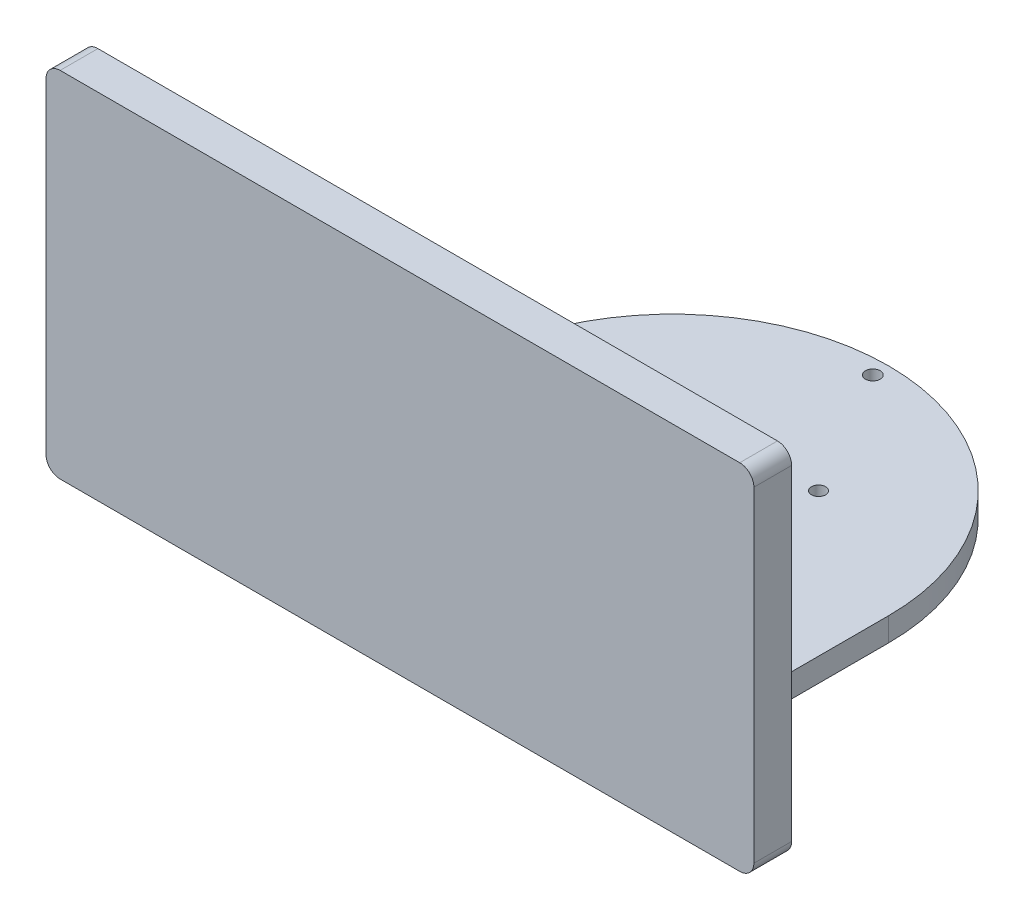
SolidWorks part; units mm, degrees
ref_plane "Front Plane" through (0, 0, 0) normal (0, 0, 1) x (1, 0, 0)
ref_plane "Top Plane" through (0, 0, 0) normal (0, 1, 0) x (1, 0, 0)
ref_plane "Right Plane" through (0, 0, 0) normal (1, 0, 0) x (0, 0, -1)
sketch "Sketch1" plane through (0, 0, 0) normal (0, 1, 0) x (1, 0, 0)
  circle A0 centre (0, 0) radius 45.85
  dimension "D1" = 91.7
extrude "Boss-Extrude1" add sketch "Sketch1" along normal blind 5
sketch "Sketch2" plane through (0, 5, 0) normal (0, 1, 0) x (1, 0, 0)
  line L0 (0, 0) -> (0, 42.5) construction
  circle A0 centre (0, 42.5) radius 1.565
  circle A1 centre (36.8061, -21.25) radius 1.565
  circle A2 centre (-36.8061, -21.25) radius 1.565
  point P11 (0, 0)
  dimension "D1" = 3.13
  dimension "D2" = 42.5
  dimension "D3" = 3
extrude "Cut-Extrude1" cut sketch "Sketch2" against normal blind 10
sketch "Sketch3" plane through (0, 5, 0) normal (0, 1, 0) x (1, 0, 0)
  line L1 (-15.5, -15.5) -> (15.5, -15.5) construction
  line L2 (-15.5, -15.5) -> (-15.5, 15.5) construction
  line L3 (-15.5, 15.5) -> (15.5, 15.5) construction
  line L4 (15.5, -15.5) -> (15.5, 15.5) construction
  line L5 (-15.5, -15.5) -> (15.5, 15.5) construction
  line L6 (-15.5, 15.5) -> (15.5, -15.5) construction
  circle A0 centre (-15.5, 15.5) radius 1.5
  circle A1 centre (15.5, 15.5) radius 1.5
  circle A2 centre (15.5, -15.5) radius 1.5
  circle A3 centre (-15.5, -15.5) radius 1.5
  circle A4 centre (0, 0) radius 7
  point P0 (0, 0)
  dimension "D3" = 3
  dimension "D1" = 31
  dimension "D2" = 31
  dimension "D4" = 2
  dimension "D5" = 2
extrude "Cut-Extrude2" cut sketch "Sketch3" against normal blind 10
sketch "Sketch4" plane through (0, 5, 0) normal (0, 1, 0) x (1, 0, 0)
  line L0 (-45.85, 0) -> (-45.85, -57.7088)
  line L1 (-45.85, -57.7088) -> (45.85, -57.7088)
  line L2 (45.85, -57.7088) -> (45.85, 0)
  circle A0 centre (0, 0) radius 45.85 construction
  arc A1 (-45.85, 0) -> (45.85, 0) centre (0, 0) ccw
extrude "Boss-Extrude2" add sketch "Sketch4" against normal up to surface (5 mm away) up to face at (-15.5, 0, 17)
sketch "Sketch5" plane through (0, 0, 0) normal (0, 1, 0) x (1, 0, 0)
  line L1 (-75, -57.7088) -> (75, -57.7088)
  line L2 (-75, -57.7088) -> (-75, -49.7088)
  line L3 (-75, -49.7088) -> (75, -49.7088)
  line L4 (75, -57.7088) -> (75, -49.7088)
  line L5 (0, 45.85) -> (0, -49.7088) construction
  arc A0 (45.85, 0) -> (-45.85, 0) centre (0, 0) ccw construction
  dimension "D1" = 8
  dimension "D2" = 150
extrude "Boss-Extrude3" add sketch "Sketch5" along normal blind 75
fillet "Fillet1" radius 3 3 edges at (0, 5, 49.7088) (45.85, 2.5, 49.7088) (-45.85, 2.5, 49.7088)
fillet "Fillet2" radius 3 4 edges at (-75, 75, 53.7088) (75, 75, 53.7088) (75, 0, 53.7088) (-75, 0, 53.7088)
